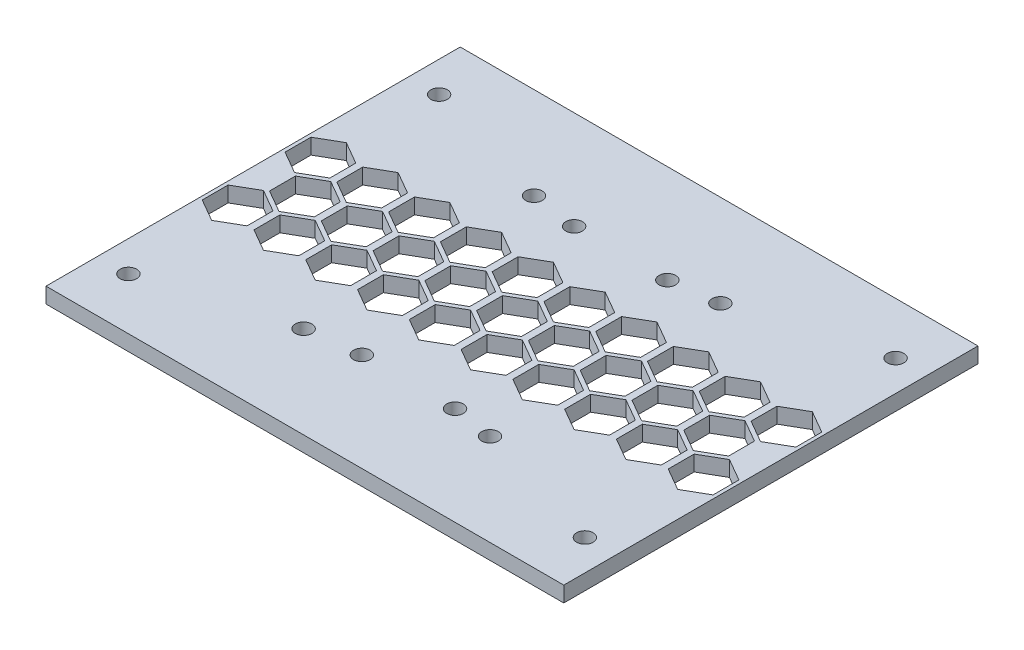
SolidWorks part; units mm, degrees
ref_plane "前视基准面" through (0, 0, 0) normal (0, 0, 1) x (1, 0, 0)
ref_plane "上视基准面" through (0, 0, 0) normal (0, 1, 0) x (1, 0, 0)
ref_plane "右视基准面" through (0, 0, 0) normal (1, 0, 0) x (0, 0, -1)
other "Configuration Table"
sketch "草图1" plane through (0, 0, 0) normal (0, 1, 0) x (1, 0, 0)
  line L0 (-18, 22.2426) -> (-18, -22.2426) construction
  line L1 (50, -40) -> (-50, -40)
  line L2 (50, -40) -> (50, 40)
  line L3 (50, 40) -> (-50, 40)
  line L4 (-50, -40) -> (-50, 40)
  line L5 (50, -40) -> (-50, 40) construction
  line L6 (50, 40) -> (-50, -40) construction
  line L7 (-18, -22.2426) -> (18, -22.2426) construction
  line L8 (-18, 22.2426) -> (18, 22.2426) construction
  line L9 (0, 51.0293) -> (0, -58.699) construction
  line L10 (-70.2205, 0) -> (76.9703, 0) construction
  line L12 (0, 5) -> (-4.3301, 2.5)
  line L13 (-4.3301, 2.5) -> (-4.3301, -2.5)
  line L14 (-4.3301, -2.5) -> (0, -5)
  line L15 (0, -5) -> (4.3301, -2.5)
  line L16 (4.3301, -2.5) -> (4.3301, 2.5)
  line L17 (4.3301, 2.5) -> (0, 5)
  line L23 (5, -3) -> (0.6699, -5.5)
  line L24 (0.6699, -5.5) -> (0.6699, -10.5)
  line L25 (0.6699, -10.5) -> (5, -13)
  line L26 (5, -13) -> (9.3301, -10.5)
  line L27 (9.3301, -10.5) -> (9.3301, -5.5)
  line L28 (9.3301, -5.5) -> (5, -3)
  line L29 (10, 5) -> (5.6699, 2.5)
  line L30 (5.6699, 2.5) -> (5.6699, -2.5)
  line L31 (5.6699, -2.5) -> (10, -5)
  line L32 (10, -5) -> (14.3301, -2.5)
  line L33 (14.3301, -2.5) -> (14.3301, 2.5)
  line L34 (14.3301, 2.5) -> (10, 5)
  line L35 (20, 5) -> (15.6699, 2.5)
  line L36 (15.6699, 2.5) -> (15.6699, -2.5)
  line L37 (15.6699, -2.5) -> (20, -5)
  line L38 (20, -5) -> (24.3301, -2.5)
  line L39 (24.3301, -2.5) -> (24.3301, 2.5)
  line L40 (24.3301, 2.5) -> (20, 5)
  line L41 (30, 5) -> (25.6699, 2.5)
  line L42 (25.6699, 2.5) -> (25.6699, -2.5)
  line L43 (25.6699, -2.5) -> (30, -5)
  line L44 (30, -5) -> (34.3301, -2.5)
  line L45 (34.3301, -2.5) -> (34.3301, 2.5)
  line L46 (34.3301, 2.5) -> (30, 5)
  line L47 (40, 5) -> (35.6699, 2.5)
  line L48 (35.6699, 2.5) -> (35.6699, -2.5)
  line L49 (35.6699, -2.5) -> (40, -5)
  line L50 (40, -5) -> (44.3301, -2.5)
  line L51 (44.3301, -2.5) -> (44.3301, 2.5)
  line L52 (44.3301, 2.5) -> (40, 5)
  line L53 (-44.3301, 2.5) -> (-40, 5)
  line L54 (-44.3301, -2.5) -> (-44.3301, 2.5)
  line L55 (-40, -5) -> (-44.3301, -2.5)
  line L56 (-35.6699, -2.5) -> (-40, -5)
  line L57 (-35.6699, 2.5) -> (-35.6699, -2.5)
  line L58 (-40, 5) -> (-35.6699, 2.5)
  line L59 (-34.3301, 2.5) -> (-30, 5)
  line L60 (-34.3301, -2.5) -> (-34.3301, 2.5)
  line L61 (-30, -5) -> (-34.3301, -2.5)
  line L62 (-25.6699, -2.5) -> (-30, -5)
  line L63 (-25.6699, 2.5) -> (-25.6699, -2.5)
  line L64 (-30, 5) -> (-25.6699, 2.5)
  line L65 (-24.3301, 2.5) -> (-20, 5)
  line L66 (-24.3301, -2.5) -> (-24.3301, 2.5)
  line L67 (-20, -5) -> (-24.3301, -2.5)
  line L68 (-15.6699, -2.5) -> (-20, -5)
  line L69 (-15.6699, 2.5) -> (-15.6699, -2.5)
  line L70 (-20, 5) -> (-15.6699, 2.5)
  line L71 (-14.3301, 2.5) -> (-10, 5)
  line L72 (-14.3301, -2.5) -> (-14.3301, 2.5)
  line L73 (-10, -5) -> (-14.3301, -2.5)
  line L74 (-5.6699, -2.5) -> (-10, -5)
  line L75 (-5.6699, 2.5) -> (-5.6699, -2.5)
  line L76 (-10, 5) -> (-5.6699, 2.5)
  line L77 (15, -3) -> (10.6699, -5.5)
  line L78 (10.6699, -5.5) -> (10.6699, -10.5)
  line L79 (10.6699, -10.5) -> (15, -13)
  line L80 (15, -13) -> (19.3301, -10.5)
  line L81 (19.3301, -10.5) -> (19.3301, -5.5)
  line L82 (19.3301, -5.5) -> (15, -3)
  line L83 (25, -3) -> (20.6699, -5.5)
  line L84 (20.6699, -5.5) -> (20.6699, -10.5)
  line L85 (20.6699, -10.5) -> (25, -13)
  line L86 (25, -13) -> (29.3301, -10.5)
  line L87 (29.3301, -10.5) -> (29.3301, -5.5)
  line L88 (29.3301, -5.5) -> (25, -3)
  line L89 (35, -3) -> (30.6699, -5.5)
  line L90 (30.6699, -5.5) -> (30.6699, -10.5)
  line L91 (30.6699, -10.5) -> (35, -13)
  line L92 (35, -13) -> (39.3301, -10.5)
  line L93 (39.3301, -10.5) -> (39.3301, -5.5)
  line L94 (39.3301, -5.5) -> (35, -3)
  line L95 (45, -3) -> (40.6699, -5.5)
  line L96 (40.6699, -5.5) -> (40.6699, -10.5)
  line L97 (40.6699, -10.5) -> (45, -13)
  line L98 (45, -13) -> (49.3301, -10.5)
  line L99 (49.3301, -10.5) -> (49.3301, -5.5)
  line L100 (49.3301, -5.5) -> (45, -3)
  line L101 (-49.3301, -5.5) -> (-45, -3)
  line L102 (-49.3301, -10.5) -> (-49.3301, -5.5)
  line L103 (-45, -13) -> (-49.3301, -10.5)
  line L104 (-40.6699, -10.5) -> (-45, -13)
  line L105 (-40.6699, -5.5) -> (-40.6699, -10.5)
  line L106 (-45, -3) -> (-40.6699, -5.5)
  line L107 (-39.3301, -5.5) -> (-35, -3)
  line L108 (-39.3301, -10.5) -> (-39.3301, -5.5)
  line L109 (-35, -13) -> (-39.3301, -10.5)
  line L110 (-30.6699, -10.5) -> (-35, -13)
  line L111 (-30.6699, -5.5) -> (-30.6699, -10.5)
  line L112 (-35, -3) -> (-30.6699, -5.5)
  line L113 (-29.3301, -5.5) -> (-25, -3)
  line L114 (-29.3301, -10.5) -> (-29.3301, -5.5)
  line L115 (-25, -13) -> (-29.3301, -10.5)
  line L116 (-20.6699, -10.5) -> (-25, -13)
  line L117 (-20.6699, -5.5) -> (-20.6699, -10.5)
  line L118 (-25, -3) -> (-20.6699, -5.5)
  line L119 (-19.3301, -5.5) -> (-15, -3)
  line L120 (-19.3301, -10.5) -> (-19.3301, -5.5)
  line L121 (-15, -13) -> (-19.3301, -10.5)
  line L122 (-10.6699, -10.5) -> (-15, -13)
  line L123 (-10.6699, -5.5) -> (-10.6699, -10.5)
  line L124 (-15, -3) -> (-10.6699, -5.5)
  line L125 (-9.3301, -5.5) -> (-5, -3)
  line L126 (-9.3301, -10.5) -> (-9.3301, -5.5)
  line L127 (-5, -13) -> (-9.3301, -10.5)
  line L128 (-0.6699, -10.5) -> (-5, -13)
  line L129 (-0.6699, -5.5) -> (-0.6699, -10.5)
  line L130 (-5, -3) -> (-0.6699, -5.5)
  line L131 (49.3301, 5.5) -> (45, 3)
  line L132 (49.3301, 10.5) -> (49.3301, 5.5)
  line L133 (45, 13) -> (49.3301, 10.5)
  line L134 (40.6699, 10.5) -> (45, 13)
  line L135 (40.6699, 5.5) -> (40.6699, 10.5)
  line L136 (45, 3) -> (40.6699, 5.5)
  line L137 (39.3301, 5.5) -> (35, 3)
  line L138 (39.3301, 10.5) -> (39.3301, 5.5)
  line L139 (35, 13) -> (39.3301, 10.5)
  line L140 (30.6699, 10.5) -> (35, 13)
  line L141 (30.6699, 5.5) -> (30.6699, 10.5)
  line L142 (35, 3) -> (30.6699, 5.5)
  line L143 (29.3301, 5.5) -> (25, 3)
  line L144 (29.3301, 10.5) -> (29.3301, 5.5)
  line L145 (25, 13) -> (29.3301, 10.5)
  line L146 (20.6699, 10.5) -> (25, 13)
  line L147 (20.6699, 5.5) -> (20.6699, 10.5)
  line L148 (25, 3) -> (20.6699, 5.5)
  line L149 (19.3301, 5.5) -> (15, 3)
  line L150 (19.3301, 10.5) -> (19.3301, 5.5)
  line L151 (15, 13) -> (19.3301, 10.5)
  line L152 (10.6699, 10.5) -> (15, 13)
  line L153 (10.6699, 5.5) -> (10.6699, 10.5)
  line L154 (15, 3) -> (10.6699, 5.5)
  line L155 (9.3301, 5.5) -> (5, 3)
  line L156 (9.3301, 10.5) -> (9.3301, 5.5)
  line L157 (5, 13) -> (9.3301, 10.5)
  line L158 (0.6699, 10.5) -> (5, 13)
  line L159 (0.6699, 5.5) -> (0.6699, 10.5)
  line L160 (5, 3) -> (0.6699, 5.5)
  line L161 (-9.3301, 10.5) -> (-9.3301, 5.5)
  line L162 (-5, 13) -> (-9.3301, 10.5)
  line L163 (-0.6699, 10.5) -> (-5, 13)
  line L164 (-0.6699, 5.5) -> (-0.6699, 10.5)
  line L165 (-5, 3) -> (-0.6699, 5.5)
  line L166 (-9.3301, 5.5) -> (-5, 3)
  line L167 (-19.3301, 10.5) -> (-19.3301, 5.5)
  line L168 (-15, 13) -> (-19.3301, 10.5)
  line L169 (-10.6699, 10.5) -> (-15, 13)
  line L170 (-10.6699, 5.5) -> (-10.6699, 10.5)
  line L171 (-15, 3) -> (-10.6699, 5.5)
  line L172 (-19.3301, 5.5) -> (-15, 3)
  line L173 (-29.3301, 10.5) -> (-29.3301, 5.5)
  line L174 (-25, 13) -> (-29.3301, 10.5)
  line L175 (-20.6699, 10.5) -> (-25, 13)
  line L176 (-20.6699, 5.5) -> (-20.6699, 10.5)
  line L177 (-25, 3) -> (-20.6699, 5.5)
  line L178 (-29.3301, 5.5) -> (-25, 3)
  line L179 (-39.3301, 10.5) -> (-39.3301, 5.5)
  line L180 (-35, 13) -> (-39.3301, 10.5)
  line L181 (-30.6699, 10.5) -> (-35, 13)
  line L182 (-30.6699, 5.5) -> (-30.6699, 10.5)
  line L183 (-35, 3) -> (-30.6699, 5.5)
  line L184 (-39.3301, 5.5) -> (-35, 3)
  line L185 (-49.3301, 10.5) -> (-49.3301, 5.5)
  line L186 (-45, 13) -> (-49.3301, 10.5)
  line L187 (-40.6699, 10.5) -> (-45, 13)
  line L188 (-40.6699, 5.5) -> (-40.6699, 10.5)
  line L189 (-45, 3) -> (-40.6699, 5.5)
  line L190 (-49.3301, 5.5) -> (-45, 3)
  circle A0 centre (-18, 22.2426) radius 1.6
  circle A1 centre (18, 22.2426) radius 1.6
  circle A2 centre (-18, -22.2426) radius 1.6
  circle A3 centre (18, -22.2426) radius 1.6
  circle A4 centre (-9, 21) radius 1.6
  circle A5 centre (9, 21) radius 1.6
  circle A6 centre (10, -21) radius 1.6
  circle A7 centre (-8, -21) radius 1.6
  circle A8 centre (-44.0808, 30) radius 1.6
  circle A9 centre (44.0808, 30) radius 1.6
  circle A10 centre (-44.0808, -30) radius 1.6
  circle A11 centre (44.0808, -30) radius 1.6
  circle A12 centre (0, 0) radius 4.3301 construction
  point P0 (0, 0)
  dimension "D3" = 3.2
  dimension "D9" = 3.2
  dimension "D18" = 3.2
  dimension "D1" = 80
  dimension "D2" = 100
  dimension "D4" = 36
  dimension "D5" = 44.4853
  dimension "D6" = 36
  dimension "D7" = 22.2426
  dimension "D8" = 18
  dimension "D10" = 18
  dimension "D11" = 18
  dimension "D12" = 42
  dimension "D13" = 42
  dimension "D14" = 9
  dimension "D15" = 21
  dimension "D16" = 21
  dimension "D17" = 8
  dimension "D19" = 10
  dimension "D20" = 5.9192
  dimension "D21" = 5
  dimension "D22" = 5
  dimension "D23" = 5
extrude "凸台-拉伸1" add sketch "草图1" along normal blind 3
